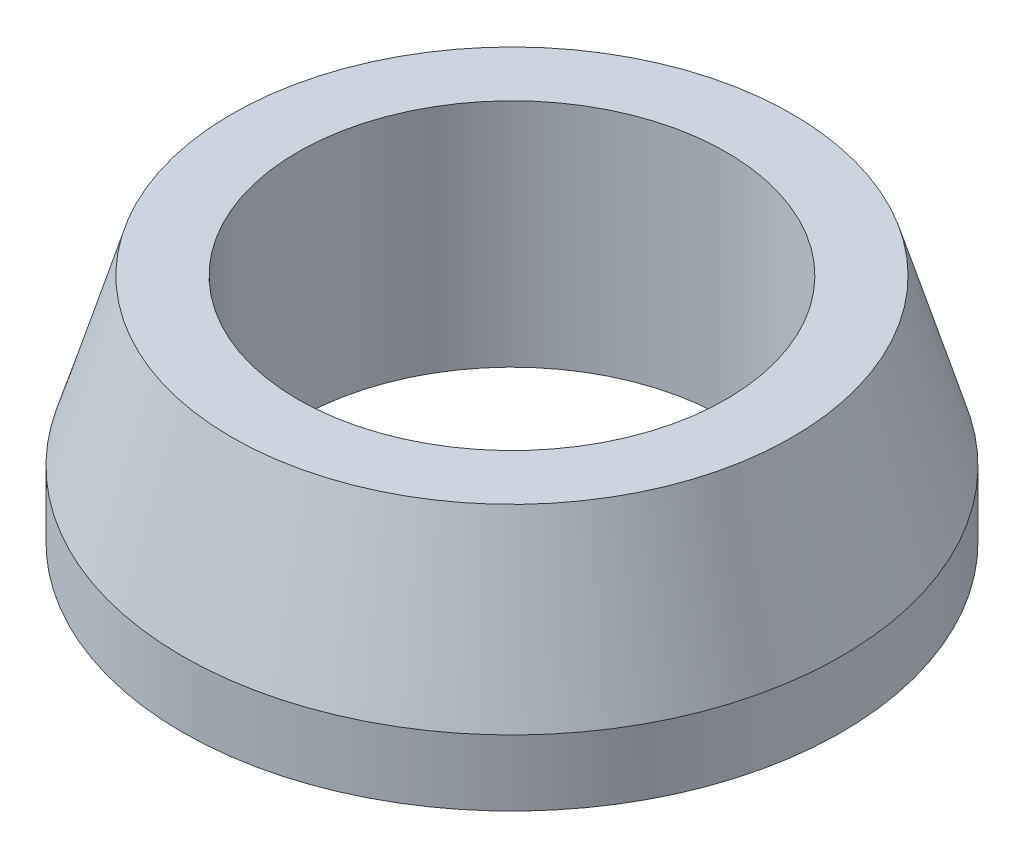
SolidWorks part; units mm, degrees
ref_plane "Płaszczyzna przednia" through (0, 0, 0) normal (0, 0, 1) x (1, 0, 0)
ref_plane "Płaszczyzna górna" through (0, 0, 0) normal (0, 1, 0) x (1, 0, 0)
ref_plane "Płaszczyzna prawa" through (0, 0, 0) normal (1, 0, 0) x (0, 0, -1)
sketch "Sketch1" plane through (0, 0, 0) normal (0, 1, 0) x (1, 0, 0)
  circle A0 centre (0, 0) radius 8.5
  circle A1 centre (0, 0) radius 6.5
  dimension "D1" = 13
  dimension "D2" = 17
ref_plane "Plane1" through (0, -5, 0) normal (0, 1, 0) x (1, 0, 0)
sketch "Sketch2" plane through (0, -5, 0) normal (0, 1, 0) x (1, 0, 0)
  circle A0 centre (0, 0) radius 6.5
  circle A1 centre (0, 0) radius 10
  dimension "D1" = 13
  dimension "D2" = 20
extrude "Boss-Extrude1" add sketch "Sketch2" against normal blind 2
loft "Loft6" add section edge at (0, -5, 10) section "Sketch1"
sketch "Sketch4" plane through (0, -5, 0) normal (0, -1, 0) x (1, 0, 0)
  circle A0 centre (0, 0) radius 6.5
  dimension "D1" = 13
extrude "Cut-Extrude1" cut sketch "Sketch4" against normal through all
equation "\"D1\"=13"
